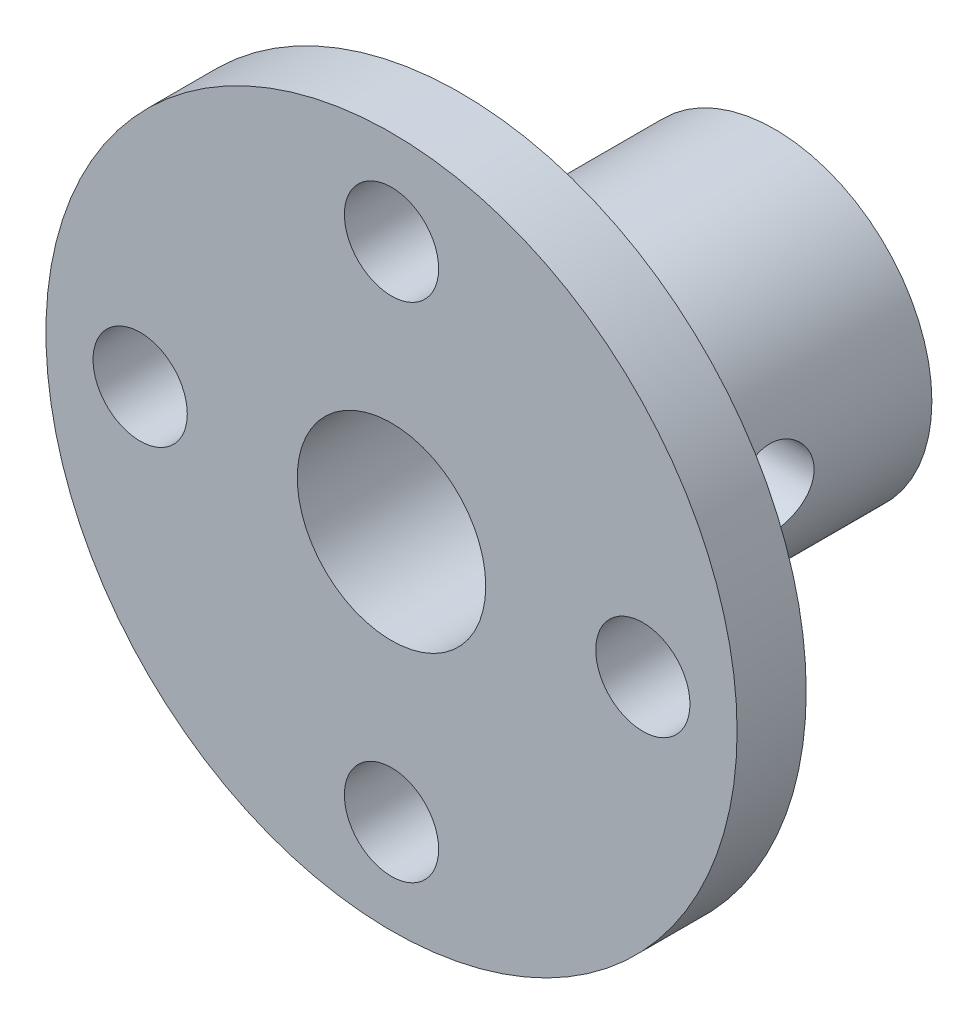
SolidWorks part; units mm, degrees
ref_plane "前视基准面" through (0, 0, 0) normal (0, 0, 1) x (1, 0, 0)
ref_plane "上视基准面" through (0, 0, 0) normal (0, 1, 0) x (1, 0, 0)
ref_plane "右视基准面" through (0, 0, 0) normal (1, 0, 0) x (0, 0, -1)
other "Configuration Table"
sketch "草图1" plane through (0, 0, 0) normal (0, 0, 1) x (1, 0, 0)
  circle A0 centre (0, 0) radius 5
  circle A1 centre (0, 0) radius 3
extrude "Hub_OD10_ID6_L10" add sketch "草图1" along normal blind 10
ref_plane "Plane_z_10_1" through (0, 0, 10) normal (0, 0, 1) x (1, 0, 0)
sketch "草图2" plane through (0, 0, 10) normal (0, 0, 1) x (1, 0, 0)
  circle A0 centre (0, 0) radius 11
  circle A1 centre (0, 0) radius 3
extrude "Flange_OD22_T2p2" add sketch "草图2" along normal blind 2.2
ref_plane "Plane_z_12.2_2" through (0, 0, 12.2) normal (0, 0, 1) x (1, 0, 0)
sketch "草图3" plane through (0, 0, 12.2) normal (0, 0, 1) x (1, 0, 0)
  circle A0 centre (8, 0) radius 1.5
  circle A1 centre (0, 8) radius 1.5
  circle A2 centre (-8, 0) radius 1.5
  circle A3 centre (0, -8) radius 1.5
extrude "4xD3_on_PCD16" cut sketch "草图3" against normal blind 2.2
ref_plane "Plane_x_5_3" through (5, 0, 0) normal (1, 0, 0) x (0, 0, -1)
sketch "草图4" plane through (5, 0, 0) normal (1, 0, 0) x (0, 0, -1)
  circle A0 centre (-5, 0) radius 1.25
extrude "M3_grub_screw_radial_reference" cut sketch "草图4" against normal blind 2.1
